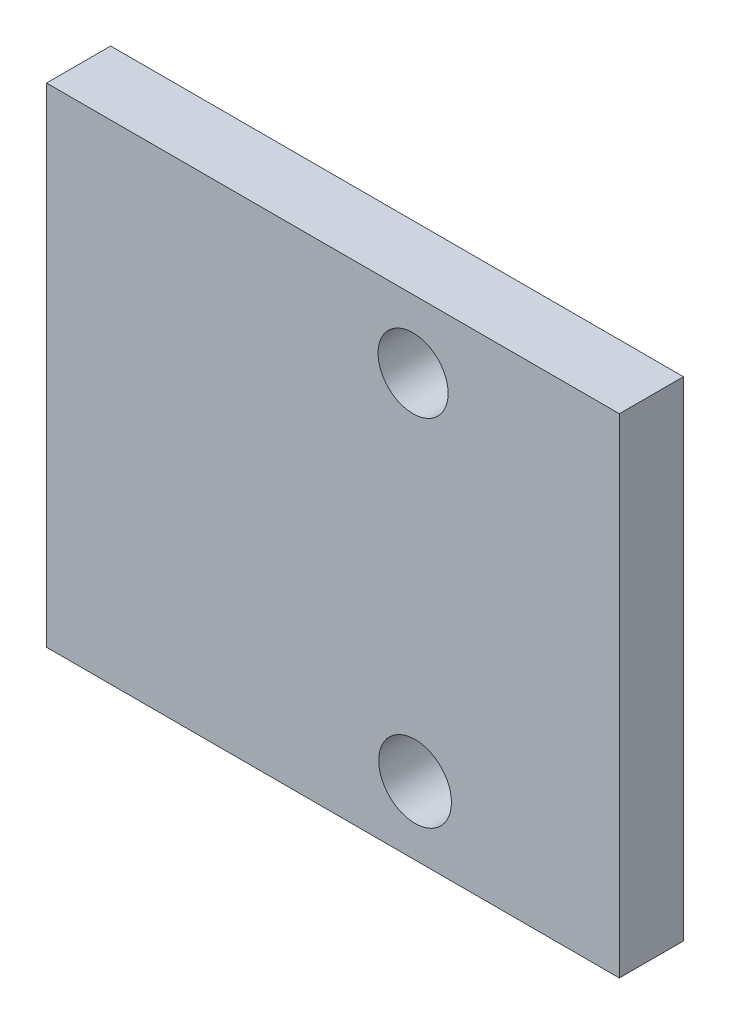
SolidWorks part; units mm, degrees
ref_plane "前视基准面" through (0, 0, 0) normal (0, 0, 1) x (1, 0, 0)
ref_plane "上视基准面" through (0, 0, 0) normal (0, 1, 0) x (1, 0, 0)
ref_plane "右视基准面" through (0, 0, 0) normal (1, 0, 0) x (0, 0, -1)
sketch "草图1" plane through (0, 0, 0) normal (0, 0, 1) x (1, 0, 0)
  line L1 (-7.15, -6.1) -> (7.15, -6.1)
  line L2 (-7.15, -6.1) -> (-7.15, 6.1)
  line L3 (-7.15, 6.1) -> (7.15, 6.1)
  line L4 (7.15, -6.1) -> (7.15, 6.1)
  line L5 (-7.15, -6.1) -> (7.15, 6.1) construction
  line L6 (-7.15, 6.1) -> (7.15, -6.1) construction
  circle A0 centre (2, 4.3999) radius 0.875
  circle A1 centre (2.05, -4.4) radius 0.9079
  point P0 (0, 0)
  dimension "D4" = 1.75
  dimension "D1" = 14.3
  dimension "D2" = 12.2
  dimension "D3" = 5.15
  dimension "D5" = 8.8
  dimension "D6" = 4.4
extrude "凸台-拉伸1" add sketch "草图1" along normal blind 1.6
sketch "草图2" plane through (0, 0, 0) normal (0, 0, -1) x (-1, 0, 0)
  line L1 (-2.5002, -2.5002) -> (2.5002, -2.5002)
  line L2 (-2.5002, -2.5002) -> (-2.5002, 2.5002)
  line L3 (-2.5002, 2.5002) -> (2.5002, 2.5002)
  line L4 (2.5002, -2.5002) -> (2.5002, 2.5002)
  line L5 (-2.5002, -2.5002) -> (2.5002, 2.5002) construction
  line L6 (-2.5002, 2.5002) -> (2.5002, -2.5002) construction
  point P0 (0, 0)
extrude "凸台-拉伸2" add sketch "草图2" along normal blind 1.6
